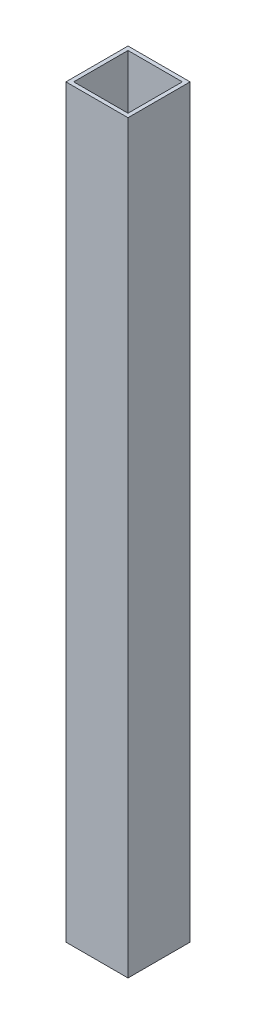
SolidWorks part; units mm, degrees
ref_plane "Front Plane" through (0, 0, 0) normal (0, 0, 1) x (1, 0, 0)
ref_plane "Top Plane" through (0, 0, 0) normal (0, 1, 0) x (1, 0, 0)
ref_plane "Right Plane" through (0, 0, 0) normal (1, 0, 0) x (0, 0, -1)
sketch "Sketch1" plane through (0, 0, 0) normal (0, 1, 0) x (1, 0, 0)
  line L0 (-22.225, 22.225) -> (22.225, 22.225)
  line L1 (-25.4, -25.4) -> (25.4, -25.4)
  line L2 (-25.4, -25.4) -> (-25.4, 25.4)
  line L3 (-25.4, 25.4) -> (25.4, 25.4)
  line L4 (25.4, -25.4) -> (25.4, 25.4)
  line L5 (-25.4, -25.4) -> (25.4, 25.4) construction
  line L6 (-25.4, 25.4) -> (25.4, -25.4) construction
  line L7 (22.225, -22.225) -> (22.225, 22.225)
  line L8 (-22.225, -22.225) -> (22.225, -22.225)
  line L9 (-22.225, -22.225) -> (-22.225, 22.225)
  point P0 (0, 0)
  dimension "D1" = 50.8
  dimension "D2" = 50.8
  dimension "D3" = 3.175
extrude "Boss-Extrude1" add sketch "Sketch1" along normal blind 609.6
